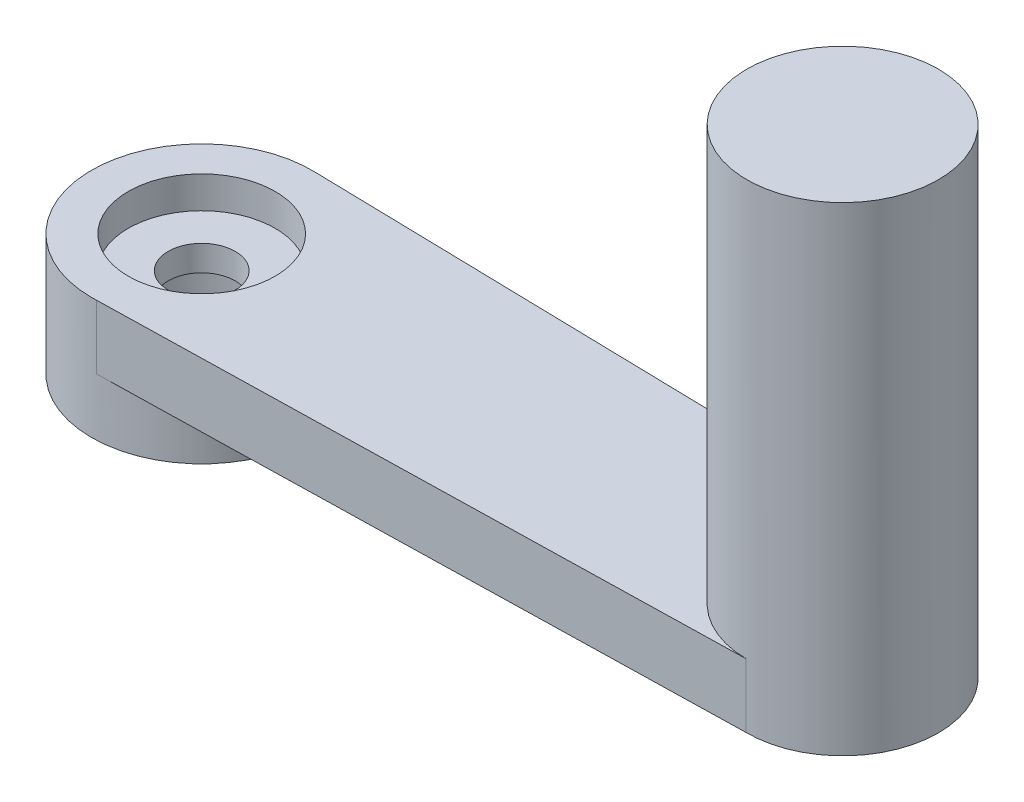
SolidWorks part; units mm, degrees
material "PVC Rígido"
ref_plane "Plano frontal" through (0, 0, 0) normal (0, 0, 1) x (1, 0, 0)
ref_plane "Plano superior" through (0, 0, 0) normal (0, 1, 0) x (1, 0, 0)
ref_plane "Plano direito" through (0, 0, 0) normal (1, 0, 0) x (0, 0, -1)
sketch "Esboço1" plane through (0, 0, 0) normal (0, 1, 0) x (1, 0, 0)
  line L0 (0, 0) -> (-14.05, 0) construction
  circle A0 centre (0, 0) radius 3.45
  dimension "D1" = 6.9
extrude "Ressalto-extrusão1" add sketch "Esboço1" against normal blind 1.4
sketch "Esboço2" plane through (0, -1.4, 0) normal (0, -1, 0) x (1, 0, 0)
  circle A1 centre (0, 0) radius 3.45
  circle A2 centre (0, 0) radius 3.45 construction
extrude "Ressalto-extrusão2" add sketch "Esboço2" along normal offset from surface (2.4 mm away) 3.8 up to face at (0, 0, 3.45)
hole_wizard "Furo1" positions "Esboço3" profile "Esboço4" legacy
sketch "Esboço3" plane through (0, -3.8, 0) normal (0, -1, 0) x (-1, 0, 0)
  point P0 (0, 0)
sketch "Esboço4" plane through (0, -3.8, 0) normal (1, 0, 0) x (0, 0, -1)
  line L0 (0, 0) -> (0, 2)
  line L1 (0, 2) -> (2.475, 2)
  line L2 (2.475, 2) -> (2.475, 0)
  line L3 (2.475, 0) -> (0, 0)
  line L4 (0, 110) -> (0, -10) construction
  dimension "Diameter" = 4.95
  dimension "Depth" = 2
hole_wizard "Furo2" positions "Esboço5" profile "Esboço6" legacy
sketch "Esboço5" plane through (0, 0, 0) normal (0, 1, 0) x (1, 0, 0)
  point P0 (0, 0)
sketch "Esboço6" plane through (0, 0, 0) normal (1, 0, 0) x (0, 0, 1)
  line L0 (0, 0) -> (0, 1)
  line L1 (0, 1) -> (2.3, 1)
  line L2 (2.3, 1) -> (2.3, 0)
  line L3 (2.3, 0) -> (0, 0)
  line L4 (0, 110) -> (0, -10) construction
  dimension "Diameter" = 4.6
  dimension "Depth" = 1
hole_wizard "Furo3" positions "Esboço7" profile "Esboço8" legacy end condition through all
sketch "Esboço7" plane through (0, 0, 0) normal (0, 1, 0) x (1, 0, 0)
  point P0 (0, 0)
sketch "Esboço8" plane through (0, 0, 0) normal (1, 0, 0) x (0, 0, 1)
  line L0 (0, 0) -> (0, 3.8)
  line L1 (0, 3.8) -> (1.05, 3.8)
  line L2 (1.05, 3.8) -> (1.05, 0)
  line L3 (1.05, 0) -> (0, 0)
  line L4 (0, 110) -> (0, -10) construction
  dimension "Diameter" = 2.1
  dimension "Depth" = 3.8
sketch "Sketch2" plane through (0, 0, 0) normal (0, 1, 0) x (1, 0, 0)
  line L0 (0, 0) -> (20, 0) construction
  line L1 (0, 3.45) -> (20.0674, 2.9992)
  line L2 (0, -3.45) -> (20.0674, -2.9992)
  line L3 (0, 4.7476) -> (0, -3.6033) construction
  circle A0 centre (0, 0) radius 3.45 construction
  arc A1 (20.0674, 2.9992) -> (20.0674, -2.9992) centre (20, 0) cw
  circle A4 centre (0, 0) radius 3.45
  arc A5 (0, -3.45) -> (0, 3.45) centre (0, 0) ccw
  circle M3 centre (0, 0) radius 3.45
  dimension "D2" = 3
  dimension "D1" = 20
  dimension "D3" = 0
extrude "Boss-Extrude1" add sketch "Sketch2" against normal blind 2 contours A1 L1 L2 M3
sketch "Sketch3" plane through (0, -2, 0) normal (0, -1, 0) x (1, 0, 0)
  line L0 (20.0674, 2.9992) -> (20.0674, -2.9992) construction
  circle A0 centre (20.0674, 0) radius 3
  point P4 (20.0674, 0)
  dimension "D1" = 6
extrude "Boss-Extrude2" add sketch "Sketch3" against normal blind 15 contours A0
sketch "Esboço11" [suppressed] plane through (0, -3.8, 0) normal (0, -1, 0) x (1, 0, 0)
  line L0 (-0.0981, 2.4731) -> (0, 2.375)
  line L1 (0, 2.375) -> (0.0981, 2.4731)
  line L2 (0, 0) -> (0, 2.475) construction
  circle A0 centre (0, 0) radius 2.375 construction
  circle A1 centre (0, 0) radius 2.475
  arc A2 (0.0981, 2.4731) -> (-0.0981, 2.4731) centre (0, 0) ccw
  dimension "D3" = 4.75
  dimension "D2" = 0.1
  dimension "D1" = 0
extrude "Ressalto-extrusão3" [suppressed] add sketch "Esboço11" against normal up to surface (2 mm away)
sketch "Sketch1" [suppressed] plane through (0, 0, 0) normal (1, 0, 0) x (0, 0, -1)
  line L0 (0, 0) -> (0, -4.3951) construction
pattern_circular "PadrãoCircular1" [suppressed] count 60 over 360
